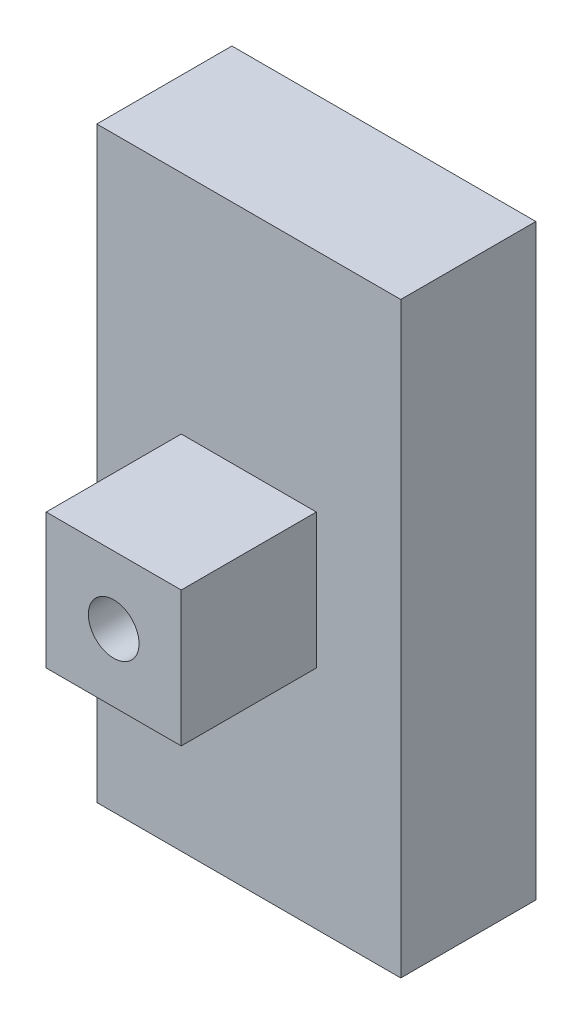
SolidWorks part; units mm, degrees
ref_plane "前视基准面" through (0, 0, 0) normal (0, 0, 1) x (1, 0, 0)
ref_plane "上视基准面" through (0, 0, 0) normal (0, 1, 0) x (1, 0, 0)
ref_plane "右视基准面" through (0, 0, 0) normal (1, 0, 0) x (0, 0, -1)
other "Configuration Table"
sketch "草图1" plane through (0, 0, 0) normal (0, 0, 1) x (1, 0, 0)
  line L1 (-45, -87) -> (-45, 87)
  line L2 (-45, -87) -> (45, -87)
  line L3 (45, -87) -> (45, 87)
  line L4 (-45, 87) -> (45, 87)
  line L5 (-45, -87) -> (45, 87) construction
  line L6 (45, -87) -> (-45, 87) construction
  point P0 (0, 0)
extrude "凸台-拉伸1" add sketch "草图1" along normal blind 40
sketch "草图2" plane through (0, 0, 40) normal (0, 0, 1) x (1, 0, 0)
  line L1 (-20, 20) -> (20, 20)
  line L2 (-20, 20) -> (-20, -20)
  line L3 (-20, -20) -> (20, -20)
  line L4 (20, 20) -> (20, -20)
  line L5 (-20, 20) -> (20, -20) construction
  line L6 (-20, -20) -> (20, 20) construction
  point P0 (0, 0)
extrude "凸台-拉伸2" add sketch "草图2" along normal blind 40
sketch "草图3" plane through (0, 0, 80) normal (0, 0, 1) x (1, 0, 0)
  circle A0 centre (0, 0) radius 7.5
extrude "切除-拉伸1" cut sketch "草图3" against normal blind 40
